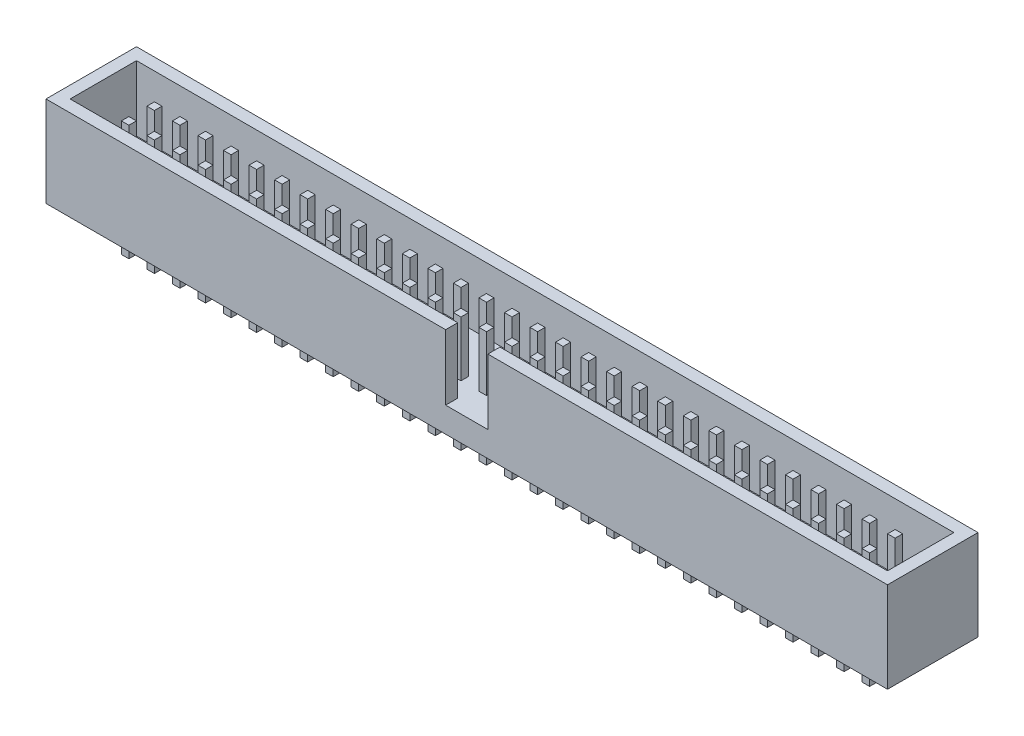
SolidWorks part; units mm, degrees
ref_plane "前视基准面" through (0, 0, 0) normal (0, 0, 1) x (1, 0, 0)
ref_plane "上视基准面" through (0, 0, 0) normal (0, 1, 0) x (1, 0, 0)
ref_plane "右视基准面" through (0, 0, 0) normal (1, 0, 0) x (0, 0, -1)
sketch "草图1" plane through (0, 0, 0) normal (0, 1, 0) x (1, 0, 0)
  line L0 (0, 85.0964) -> (0, -118.2031) construction
  line L1 (-41.84, 4.5) -> (41.84, 4.5)
  line L2 (-41.84, 4.5) -> (-41.84, -4.5)
  line L3 (-41.84, -4.5) -> (41.84, -4.5)
  line L4 (41.84, 4.5) -> (41.84, -4.5)
  line L5 (-200.5452, 0) -> (261.2352, 0) construction
  dimension "D1" = 9
  dimension "D2" = 83.68
extrude "拉伸1" add sketch "草图1" along normal blind 9
sketch "草图2" plane through (0, 9, 0) normal (0, 1, 0) x (-1, 0, 0)
  line L8 (-40.64, 3.3) -> (-40.64, -3.3)
  line L9 (40.64, 3.3) -> (-40.64, 3.3)
  line L10 (40.64, -3.3) -> (40.64, 3.3)
  line L11 (-40.64, -3.3) -> (40.64, -3.3)
  line L12 (-40.64, 3.3) -> (-40.64, -3.3)
  line L13 (40.64, 3.3) -> (-40.64, 3.3)
  line L14 (40.64, -3.3) -> (40.64, 3.3)
  line L15 (-40.64, -3.3) -> (40.64, -3.3)
  dimension "D1" = 1.2
extrude "切除-拉伸1" cut sketch "草图2" against normal blind 6.5
sketch "草图3" plane through (0, 0, 4.5) normal (0, 0, 1) x (1, 0, 0)
  line L0 (-41.84, 9) -> (41.84, 9) construction
  line L1 (-2.1, 9) -> (2.1, 9)
  line L2 (-2.1, 9) -> (-2.1, 2.5)
  line L3 (-2.1, 2.5) -> (2.1, 2.5)
  line L4 (2.1, 9) -> (2.1, 2.5)
  line L5 (-40.64, 2.5) -> (40.64, 2.5) construction
  line L6 (0, 9.4226) -> (0, -4.0288) construction
  dimension "D1" = 4.2
extrude "切除-拉伸2" cut sketch "草图3" against normal blind 6.5
sketch "草图5" plane through (0, 0, 0) normal (0, -1, 0) x (1, 0, 0)
  line L0 (0, 6.0683) -> (0, -6.9786) construction
  line L1 (-14.7999, 0) -> (15.2382, 0) construction
  line L2 (-1.27, 2.5244) -> (-1.27, -0.4442) construction
  line L3 (-1.645, 0.895) -> (-0.895, 0.895)
  line L4 (-1.645, 0.895) -> (-1.645, 1.645)
  line L5 (-1.645, 1.645) -> (-0.895, 1.645)
  line L6 (-0.895, 0.895) -> (-0.895, 1.645)
  line L7 (-2.3518, 1.27) -> (0.5396, 1.27) construction
  line L8 (4.185, -0.895) -> (3.435, -0.895)
  line L9 (4.185, -0.895) -> (4.185, -1.645)
  line L10 (4.185, -1.645) -> (3.435, -1.645)
  line L11 (3.435, -0.895) -> (3.435, -1.645)
  line L12 (3.435, 0.895) -> (3.435, 1.645)
  line L13 (4.185, 1.645) -> (3.435, 1.645)
  line L14 (4.185, 0.895) -> (4.185, 1.645)
  line L15 (4.185, 0.895) -> (3.435, 0.895)
  line L16 (3.81, 2.5244) -> (3.81, -0.4442) construction
  line L17 (6.725, -0.895) -> (5.975, -0.895)
  line L18 (6.725, -0.895) -> (6.725, -1.645)
  line L19 (6.725, -1.645) -> (5.975, -1.645)
  line L20 (5.975, -0.895) -> (5.975, -1.645)
  line L21 (5.975, 0.895) -> (5.975, 1.645)
  line L22 (6.725, 1.645) -> (5.975, 1.645)
  line L23 (6.725, 0.895) -> (6.725, 1.645)
  line L24 (6.725, 0.895) -> (5.975, 0.895)
  line L25 (6.35, 2.5244) -> (6.35, -0.4442) construction
  line L26 (9.265, -0.895) -> (8.515, -0.895)
  line L27 (9.265, -0.895) -> (9.265, -1.645)
  line L28 (9.265, -1.645) -> (8.515, -1.645)
  line L29 (8.515, -0.895) -> (8.515, -1.645)
  line L30 (8.515, 0.895) -> (8.515, 1.645)
  line L31 (9.265, 1.645) -> (8.515, 1.645)
  line L32 (-0.895, -0.895) -> (-0.895, -1.645)
  line L33 (-1.645, -1.645) -> (-0.895, -1.645)
  line L34 (-1.645, -0.895) -> (-1.645, -1.645)
  line L35 (-1.645, -0.895) -> (-0.895, -0.895)
  line L36 (1.27, 2.5244) -> (1.27, -0.4442) construction
  line L37 (1.645, -0.895) -> (0.895, -0.895)
  line L38 (1.645, -0.895) -> (1.645, -1.645)
  line L39 (1.645, -1.645) -> (0.895, -1.645)
  line L40 (0.895, -0.895) -> (0.895, -1.645)
  line L41 (9.265, 0.895) -> (9.265, 1.645)
  line L42 (9.265, 0.895) -> (8.515, 0.895)
  line L43 (8.89, 2.5244) -> (8.89, -0.4442) construction
  line L44 (11.805, -0.895) -> (11.055, -0.895)
  line L45 (11.805, -0.895) -> (11.805, -1.645)
  line L46 (11.805, -1.645) -> (11.055, -1.645)
  line L47 (11.055, -0.895) -> (11.055, -1.645)
  line L48 (11.055, 0.895) -> (11.055, 1.645)
  line L49 (11.805, 1.645) -> (11.055, 1.645)
  line L50 (11.805, 0.895) -> (11.805, 1.645)
  line L51 (11.805, 0.895) -> (11.055, 0.895)
  line L52 (11.43, 2.5244) -> (11.43, -0.4442) construction
  line L53 (14.345, -0.895) -> (13.595, -0.895)
  line L54 (14.345, -0.895) -> (14.345, -1.645)
  line L55 (14.345, -1.645) -> (13.595, -1.645)
  line L56 (13.595, -0.895) -> (13.595, -1.645)
  line L57 (13.595, 0.895) -> (13.595, 1.645)
  line L58 (14.345, 1.645) -> (13.595, 1.645)
  line L59 (14.345, 0.895) -> (14.345, 1.645)
  line L60 (14.345, 0.895) -> (13.595, 0.895)
  line L61 (13.97, 2.5244) -> (13.97, -0.4442) construction
  line L62 (16.885, -0.895) -> (16.135, -0.895)
  line L63 (16.885, -0.895) -> (16.885, -1.645)
  line L64 (16.885, -1.645) -> (16.135, -1.645)
  line L65 (0.895, 0.895) -> (0.895, 1.645)
  line L66 (1.645, 1.645) -> (0.895, 1.645)
  line L67 (1.645, 0.895) -> (1.645, 1.645)
  line L68 (1.645, 0.895) -> (0.895, 0.895)
  line L69 (16.135, -0.895) -> (16.135, -1.645)
  line L70 (16.135, 0.895) -> (16.135, 1.645)
  line L71 (16.885, 1.645) -> (16.135, 1.645)
  line L72 (16.885, 0.895) -> (16.885, 1.645)
  line L73 (16.885, 0.895) -> (16.135, 0.895)
  line L74 (16.51, 2.5244) -> (16.51, -0.4442) construction
  line L75 (19.425, -0.895) -> (18.675, -0.895)
  line L76 (19.425, -0.895) -> (19.425, -1.645)
  line L77 (19.425, -1.645) -> (18.675, -1.645)
  line L78 (18.675, -0.895) -> (18.675, -1.645)
  line L79 (18.675, 0.895) -> (18.675, 1.645)
  line L80 (19.425, 1.645) -> (18.675, 1.645)
  line L81 (19.425, 0.895) -> (19.425, 1.645)
  line L82 (19.425, 0.895) -> (18.675, 0.895)
  line L83 (19.05, 2.5244) -> (19.05, -0.4442) construction
  line L84 (21.965, -0.895) -> (21.215, -0.895)
  line L85 (21.965, -0.895) -> (21.965, -1.645)
  line L86 (21.965, -1.645) -> (21.215, -1.645)
  line L87 (21.215, -0.895) -> (21.215, -1.645)
  line L88 (21.215, 0.895) -> (21.215, 1.645)
  line L89 (21.965, 1.645) -> (21.215, 1.645)
  line L90 (21.965, 0.895) -> (21.965, 1.645)
  line L91 (21.965, 0.895) -> (21.215, 0.895)
  line L92 (21.59, 2.5244) -> (21.59, -0.4442) construction
  line L93 (24.505, -0.895) -> (23.755, -0.895)
  line L94 (24.505, -0.895) -> (24.505, -1.645)
  line L95 (24.505, -1.645) -> (23.755, -1.645)
  line L96 (23.755, -0.895) -> (23.755, -1.645)
  line L97 (23.755, 0.895) -> (23.755, 1.645)
  line L98 (24.505, 1.645) -> (23.755, 1.645)
  line L99 (24.505, 0.895) -> (24.505, 1.645)
  line L100 (24.505, 0.895) -> (23.755, 0.895)
  line L101 (24.13, 2.5244) -> (24.13, -0.4442) construction
  line L102 (27.045, -0.895) -> (26.295, -0.895)
  line L103 (27.045, -0.895) -> (27.045, -1.645)
  line L104 (27.045, -1.645) -> (26.295, -1.645)
  line L105 (26.295, -0.895) -> (26.295, -1.645)
  line L106 (26.295, 0.895) -> (26.295, 1.645)
  line L107 (27.045, 1.645) -> (26.295, 1.645)
  line L108 (27.045, 0.895) -> (27.045, 1.645)
  line L109 (27.045, 0.895) -> (26.295, 0.895)
  line L110 (26.67, 2.5244) -> (26.67, -0.4442) construction
  line L111 (29.585, -0.895) -> (28.835, -0.895)
  line L112 (29.585, -0.895) -> (29.585, -1.645)
  line L113 (29.585, -1.645) -> (28.835, -1.645)
  line L114 (28.835, -0.895) -> (28.835, -1.645)
  line L115 (28.835, 0.895) -> (28.835, 1.645)
  line L116 (29.585, 1.645) -> (28.835, 1.645)
  line L117 (29.585, 0.895) -> (29.585, 1.645)
  line L118 (29.585, 0.895) -> (28.835, 0.895)
  line L119 (29.21, 2.5244) -> (29.21, -0.4442) construction
  line L120 (32.125, -0.895) -> (31.375, -0.895)
  line L121 (32.125, -0.895) -> (32.125, -1.645)
  line L122 (32.125, -1.645) -> (31.375, -1.645)
  line L123 (31.375, -0.895) -> (31.375, -1.645)
  line L124 (31.375, 0.895) -> (31.375, 1.645)
  line L125 (32.125, 1.645) -> (31.375, 1.645)
  line L126 (32.125, 0.895) -> (32.125, 1.645)
  line L127 (32.125, 0.895) -> (31.375, 0.895)
  line L128 (31.75, 2.5244) -> (31.75, -0.4442) construction
  line L129 (34.665, -0.895) -> (33.915, -0.895)
  line L130 (34.665, -0.895) -> (34.665, -1.645)
  line L131 (34.665, -1.645) -> (33.915, -1.645)
  line L132 (33.915, -0.895) -> (33.915, -1.645)
  line L133 (33.915, 0.895) -> (33.915, 1.645)
  line L134 (34.665, 1.645) -> (33.915, 1.645)
  line L135 (34.665, 0.895) -> (34.665, 1.645)
  line L136 (34.665, 0.895) -> (33.915, 0.895)
  line L137 (34.29, 2.5244) -> (34.29, -0.4442) construction
  line L138 (37.205, -0.895) -> (36.455, -0.895)
  line L139 (37.205, -0.895) -> (37.205, -1.645)
  line L140 (37.205, -1.645) -> (36.455, -1.645)
  line L141 (36.455, -0.895) -> (36.455, -1.645)
  line L142 (36.455, 0.895) -> (36.455, 1.645)
  line L143 (37.205, 1.645) -> (36.455, 1.645)
  line L144 (37.205, 0.895) -> (37.205, 1.645)
  line L145 (37.205, 0.895) -> (36.455, 0.895)
  line L146 (36.83, 2.5244) -> (36.83, -0.4442) construction
  line L147 (-4.185, 0.895) -> (-3.435, 0.895)
  line L148 (-4.185, 0.895) -> (-4.185, 1.645)
  line L149 (-4.185, 1.645) -> (-3.435, 1.645)
  line L150 (-3.435, 0.895) -> (-3.435, 1.645)
  line L151 (-3.435, -0.895) -> (-3.435, -1.645)
  line L152 (-4.185, -1.645) -> (-3.435, -1.645)
  line L153 (-4.185, -0.895) -> (-4.185, -1.645)
  line L154 (-4.185, -0.895) -> (-3.435, -0.895)
  line L155 (-3.81, 2.5244) -> (-3.81, -0.4442) construction
  line L156 (-6.725, 0.895) -> (-5.975, 0.895)
  line L157 (-6.725, 0.895) -> (-6.725, 1.645)
  line L158 (-6.725, 1.645) -> (-5.975, 1.645)
  line L159 (-5.975, 0.895) -> (-5.975, 1.645)
  line L160 (-5.975, -0.895) -> (-5.975, -1.645)
  line L161 (-6.725, -1.645) -> (-5.975, -1.645)
  line L162 (-6.725, -0.895) -> (-6.725, -1.645)
  line L163 (-6.725, -0.895) -> (-5.975, -0.895)
  line L164 (-6.35, 2.5244) -> (-6.35, -0.4442) construction
  line L165 (-9.265, 0.895) -> (-8.515, 0.895)
  line L166 (-9.265, 0.895) -> (-9.265, 1.645)
  line L167 (-9.265, 1.645) -> (-8.515, 1.645)
  line L168 (-8.515, 0.895) -> (-8.515, 1.645)
  line L169 (-8.515, -0.895) -> (-8.515, -1.645)
  line L170 (-9.265, -1.645) -> (-8.515, -1.645)
  line L171 (-9.265, -0.895) -> (-9.265, -1.645)
  line L172 (-9.265, -0.895) -> (-8.515, -0.895)
  line L173 (-8.89, 2.5244) -> (-8.89, -0.4442) construction
  line L174 (-11.805, 0.895) -> (-11.055, 0.895)
  line L175 (-11.805, 0.895) -> (-11.805, 1.645)
  line L176 (-11.805, 1.645) -> (-11.055, 1.645)
  line L177 (-11.055, 0.895) -> (-11.055, 1.645)
  line L178 (-11.055, -0.895) -> (-11.055, -1.645)
  line L179 (-11.805, -1.645) -> (-11.055, -1.645)
  line L180 (-11.805, -0.895) -> (-11.805, -1.645)
  line L181 (-11.805, -0.895) -> (-11.055, -0.895)
  line L182 (-11.43, 2.5244) -> (-11.43, -0.4442) construction
  line L183 (-14.345, 0.895) -> (-13.595, 0.895)
  line L184 (-14.345, 0.895) -> (-14.345, 1.645)
  line L185 (-14.345, 1.645) -> (-13.595, 1.645)
  line L186 (-13.595, 0.895) -> (-13.595, 1.645)
  line L187 (-13.595, -0.895) -> (-13.595, -1.645)
  line L188 (-14.345, -1.645) -> (-13.595, -1.645)
  line L189 (-14.345, -0.895) -> (-14.345, -1.645)
  line L190 (-14.345, -0.895) -> (-13.595, -0.895)
  line L191 (-13.97, 2.5244) -> (-13.97, -0.4442) construction
  line L192 (-16.885, 0.895) -> (-16.135, 0.895)
  line L193 (-16.885, 0.895) -> (-16.885, 1.645)
  line L194 (-16.885, 1.645) -> (-16.135, 1.645)
  line L195 (-16.135, 0.895) -> (-16.135, 1.645)
  line L196 (-16.135, -0.895) -> (-16.135, -1.645)
  line L197 (-16.885, -1.645) -> (-16.135, -1.645)
  line L198 (-16.885, -0.895) -> (-16.885, -1.645)
  line L199 (-16.885, -0.895) -> (-16.135, -0.895)
  line L200 (-16.51, 2.5244) -> (-16.51, -0.4442) construction
  line L201 (-19.425, 0.895) -> (-18.675, 0.895)
  line L202 (-19.425, 0.895) -> (-19.425, 1.645)
  line L203 (-19.425, 1.645) -> (-18.675, 1.645)
  line L204 (-18.675, 0.895) -> (-18.675, 1.645)
  line L205 (-18.675, -0.895) -> (-18.675, -1.645)
  line L206 (-19.425, -1.645) -> (-18.675, -1.645)
  line L207 (-19.425, -0.895) -> (-19.425, -1.645)
  line L208 (-19.425, -0.895) -> (-18.675, -0.895)
  line L209 (-19.05, 2.5244) -> (-19.05, -0.4442) construction
  line L210 (-21.965, 0.895) -> (-21.215, 0.895)
  line L211 (-21.965, 0.895) -> (-21.965, 1.645)
  line L212 (-21.965, 1.645) -> (-21.215, 1.645)
  line L213 (-21.215, 0.895) -> (-21.215, 1.645)
  line L214 (-21.215, -0.895) -> (-21.215, -1.645)
  line L215 (-21.965, -1.645) -> (-21.215, -1.645)
  line L216 (-21.965, -0.895) -> (-21.965, -1.645)
  line L217 (-21.965, -0.895) -> (-21.215, -0.895)
  line L218 (-21.59, 2.5244) -> (-21.59, -0.4442) construction
  line L219 (-24.505, 0.895) -> (-23.755, 0.895)
  line L220 (-24.505, 0.895) -> (-24.505, 1.645)
  line L221 (-24.505, 1.645) -> (-23.755, 1.645)
  line L222 (-23.755, 0.895) -> (-23.755, 1.645)
  line L223 (-23.755, -0.895) -> (-23.755, -1.645)
  line L224 (-24.505, -1.645) -> (-23.755, -1.645)
  line L225 (-24.505, -0.895) -> (-24.505, -1.645)
  line L226 (-24.505, -0.895) -> (-23.755, -0.895)
  line L227 (-24.13, 2.5244) -> (-24.13, -0.4442) construction
  line L228 (-27.045, 0.895) -> (-26.295, 0.895)
  line L229 (-27.045, 0.895) -> (-27.045, 1.645)
  line L230 (-27.045, 1.645) -> (-26.295, 1.645)
  line L231 (-26.295, 0.895) -> (-26.295, 1.645)
  line L232 (-26.295, -0.895) -> (-26.295, -1.645)
  line L233 (-27.045, -1.645) -> (-26.295, -1.645)
  line L234 (-27.045, -0.895) -> (-27.045, -1.645)
  line L235 (-27.045, -0.895) -> (-26.295, -0.895)
  line L236 (-26.67, 2.5244) -> (-26.67, -0.4442) construction
  line L237 (-29.585, 0.895) -> (-28.835, 0.895)
  line L238 (-29.585, 0.895) -> (-29.585, 1.645)
  line L239 (-29.585, 1.645) -> (-28.835, 1.645)
  line L240 (-28.835, 0.895) -> (-28.835, 1.645)
  line L241 (-28.835, -0.895) -> (-28.835, -1.645)
  line L242 (-29.585, -1.645) -> (-28.835, -1.645)
  line L243 (-29.585, -0.895) -> (-29.585, -1.645)
  line L244 (-29.585, -0.895) -> (-28.835, -0.895)
  line L245 (-29.21, 2.5244) -> (-29.21, -0.4442) construction
  line L246 (-32.125, 0.895) -> (-31.375, 0.895)
  line L247 (-32.125, 0.895) -> (-32.125, 1.645)
  line L248 (-32.125, 1.645) -> (-31.375, 1.645)
  line L249 (-31.375, 0.895) -> (-31.375, 1.645)
  line L250 (-31.375, -0.895) -> (-31.375, -1.645)
  line L251 (-32.125, -1.645) -> (-31.375, -1.645)
  line L252 (-32.125, -0.895) -> (-32.125, -1.645)
  line L253 (-32.125, -0.895) -> (-31.375, -0.895)
  line L254 (-31.75, 2.5244) -> (-31.75, -0.4442) construction
  line L255 (-34.665, 0.895) -> (-33.915, 0.895)
  line L256 (-34.665, 0.895) -> (-34.665, 1.645)
  line L257 (-34.665, 1.645) -> (-33.915, 1.645)
  line L258 (-33.915, 0.895) -> (-33.915, 1.645)
  line L259 (-33.915, -0.895) -> (-33.915, -1.645)
  line L260 (-34.665, -1.645) -> (-33.915, -1.645)
  line L261 (-34.665, -0.895) -> (-34.665, -1.645)
  line L262 (-34.665, -0.895) -> (-33.915, -0.895)
  line L263 (-34.29, 2.5244) -> (-34.29, -0.4442) construction
  line L264 (-37.205, 0.895) -> (-36.455, 0.895)
  line L265 (-37.205, 0.895) -> (-37.205, 1.645)
  line L266 (-37.205, 1.645) -> (-36.455, 1.645)
  line L267 (-36.455, 0.895) -> (-36.455, 1.645)
  line L268 (-36.455, -0.895) -> (-36.455, -1.645)
  line L269 (-37.205, -1.645) -> (-36.455, -1.645)
  line L270 (-37.205, -0.895) -> (-37.205, -1.645)
  line L271 (-37.205, -0.895) -> (-36.455, -0.895)
  line L272 (-36.83, 2.5244) -> (-36.83, -0.4442) construction
  dimension "D1" = 0.75
  dimension "D2" = 15
  dimension "D3" = 1.27
  dimension "D4" = 1.27
  dimension "D5" = 15
extrude "拉伸2" add sketch "草图5" along normal blind 3.5 and the other way offset from surface (8 mm away) 1 other way up to face at (0, 9, 1.3)
sketch "草图6" plane through (0, 0, 0) normal (0, -1, 0) x (1, 0, 0)
  line L0 (34.2898, 0) -> (-33.2336, 0) construction
  line L1 (0, 6.8981) -> (0, -7.2913) construction
  line L10 (24.505, 0.895) -> (24.505, 1.645) construction
  line L11 (24.505, 1.645) -> (23.755, 1.645) construction
  line L13 (23.755, 0.895) -> (24.505, 0.895) construction
  circle A0 centre (24.13, 1.27) radius 0.375
